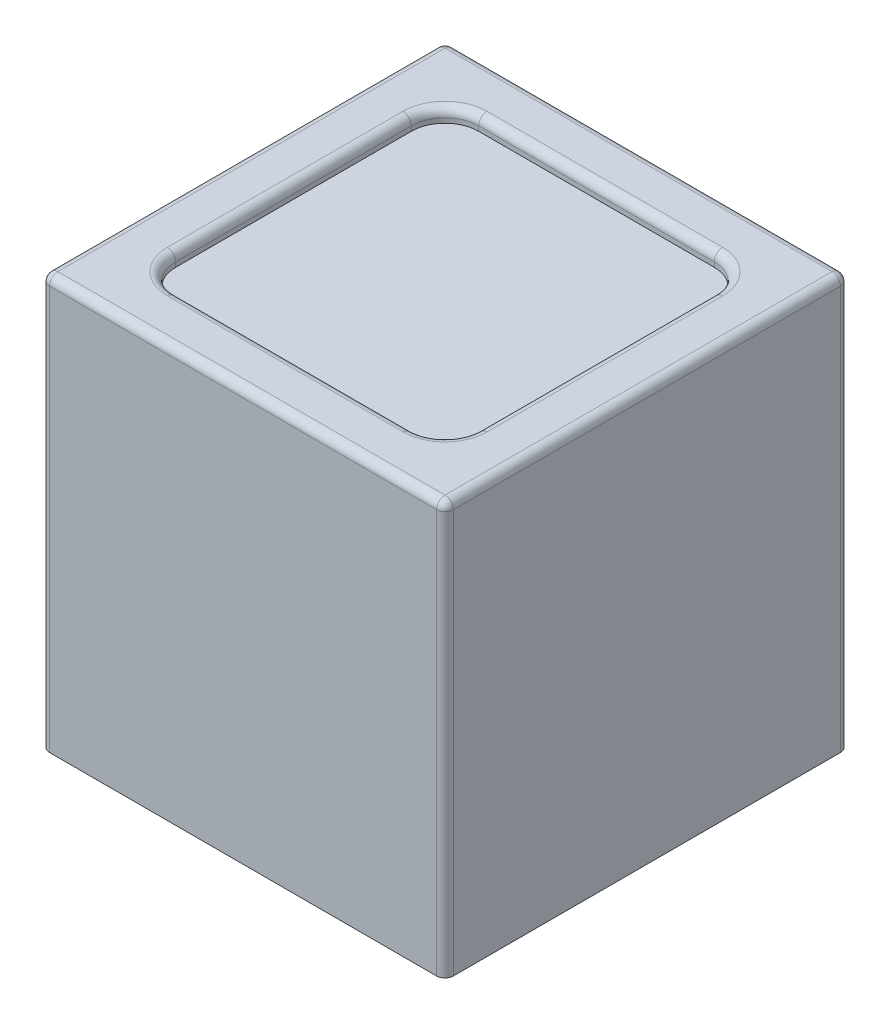
SolidWorks part; units mm, degrees
ref_plane "前视基准面" through (0, 0, 0) normal (0, 0, 1) x (1, 0, 0)
ref_plane "上视基准面" through (0, 0, 0) normal (0, 1, 0) x (1, 0, 0)
ref_plane "右视基准面" through (0, 0, 0) normal (1, 0, 0) x (0, 0, -1)
other "Configuration Table"
sketch "草图1" plane through (0, 0, 0) normal (0, 1, 0) x (1, 0, 0)
  line L1 (-110, -110) -> (110, -110)
  line L2 (-110, -110) -> (-110, 110)
  line L3 (-110, 110) -> (110, 110)
  line L4 (110, -110) -> (110, 110)
  line L5 (-110, -110) -> (110, 110) construction
  line L6 (-110, 110) -> (110, -110) construction
  point P0 (0, 0)
  dimension "D1" = 220
  dimension "D2" = 220
extrude "拉伸-薄壁1" add sketch "草图1" along normal blind 230 thin
sketch "草图2" plane through (0, 230, 0) normal (0, 1, 0) x (1, 0, 0)
  line L1 (-120, 120) -> (120, 120)
  line L2 (-120, 120) -> (-120, -120)
  line L3 (-120, -120) -> (120, -120)
  line L4 (120, 120) -> (120, -120)
extrude "凸台-拉伸1" add sketch "草图2" along normal blind 15
sketch "草图3" plane through (0, 0, 0) normal (0, -1, 0) x (1, 0, 0)
  line L1 (-120, -120) -> (120, -120)
  line L2 (-120, -120) -> (-120, 120)
  line L3 (-120, 120) -> (120, 120)
  line L4 (120, -120) -> (120, 120)
sketch "草图5" plane through (0, 230, 0) normal (0, -1, 0) x (1, 0, 0)
  line L1 (-90, 110) -> (90, 110)
  line L2 (-110, 90) -> (-110, -90)
  line L3 (-90, -110) -> (90, -110)
  line L4 (110, 90) -> (110, -90)
  line L5 (-120, -120) -> (120, -120)
  line L6 (-120, -120) -> (-120, 120)
  line L7 (-120, 120) -> (120, 120)
  line L8 (120, -120) -> (120, 120)
  arc A0 (90, 110) -> (110, 90) centre (90, 90) cw
  arc A1 (90, -110) -> (110, -90) centre (90, -90) ccw
  arc A2 (-110, -90) -> (-90, -110) centre (-90, -90) ccw
  arc A3 (-90, 110) -> (-110, 90) centre (-90, 90) ccw
  point P10 (110, -110)
  point P15 (-110, 110)
  dimension "D1" = 20
extrude "凸台-拉伸3" add sketch "草图5" along normal blind 230 contours L6 L5 L8 L7 | L2 A2 L3 A1 L4 A0 L1 A3
fillet "圆角1" radius 5 8 edges at (0, 245, 120) (-120, 245, 0) (-120, 122.5, 120) (120, 122.5, 120) (120, 245, 0) (120, 122.5, -120) (0, 245, -120) (-120, 122.5, -120)
fillet "圆角2" radius 5 8 edges at (104.1421, 230, 104.1421) (110, 230, 0) (104.1421, 230, -104.1421) (0, 230, -110) (-104.1421, 230, -104.1421) (-110, 230, 0) (-104.1421, 230, 104.1421) (0, 230, 110)
sketch "草图6" plane through (0, 245, 0) normal (0, 1, 0) x (1, 0, 0)
  line L1 (-70, -90) -> (70, -90)
  line L2 (-90, -70) -> (-90, 70)
  line L3 (-70, 90) -> (70, 90)
  line L4 (90, -70) -> (90, 70)
  line L5 (-90, -90) -> (90, 90) construction
  line L6 (-90, 90) -> (90, -90) construction
  arc A0 (-70, -90) -> (-90, -70) centre (-70, -70) cw
  arc A1 (70, -90) -> (90, -70) centre (70, -70) ccw
  arc A2 (70, 90) -> (90, 70) centre (70, 70) cw
  arc A3 (-90, 70) -> (-70, 90) centre (-70, 70) cw
  point P0 (0, 0)
  dimension "D3" = 20
  dimension "D1" = 180
  dimension "D2" = 180
extrude "切除-拉伸2" cut sketch "草图6" against normal blind 230
sketch "草图9" plane through (0, 0, -120) normal (0, 0, -1) x (-1, 0, 0)
  line L1 (-107.1321, 237.2197) -> (107.1321, 237.2197)
  line L2 (-107.1321, 237.2197) -> (-107.1321, 234.5017)
  line L3 (-107.1321, 234.5017) -> (107.1321, 234.5017)
  line L4 (107.1321, 237.2197) -> (107.1321, 234.5017)
  line L5 (-107.1321, 237.2197) -> (107.1321, 234.5017) construction
  line L6 (-107.1321, 234.5017) -> (107.1321, 237.2197) construction
  point P0 (0, 235.8607)
extrude "凸台-拉伸5" add sketch "草图9" against normal blind 235 separate body
fillet "圆角3" radius 5 16 edges at (-84.1421, 245, -84.1421) (0, 245, -90) (84.1421, 245, -84.1421) (90, 245, 0) (84.1421, 245, 84.1421) (0, 245, 90) (-84.1421, 245, 84.1421) (-84.1421, 230, -84.1421) (0, 230, -90) (84.1421, 230, -84.1421) (90, 230, 0) (84.1421, 230, 84.1421) (0, 230, 90) (-84.1421, 230, 84.1421) (-90, 245, 0) (-90, 230, 0)
